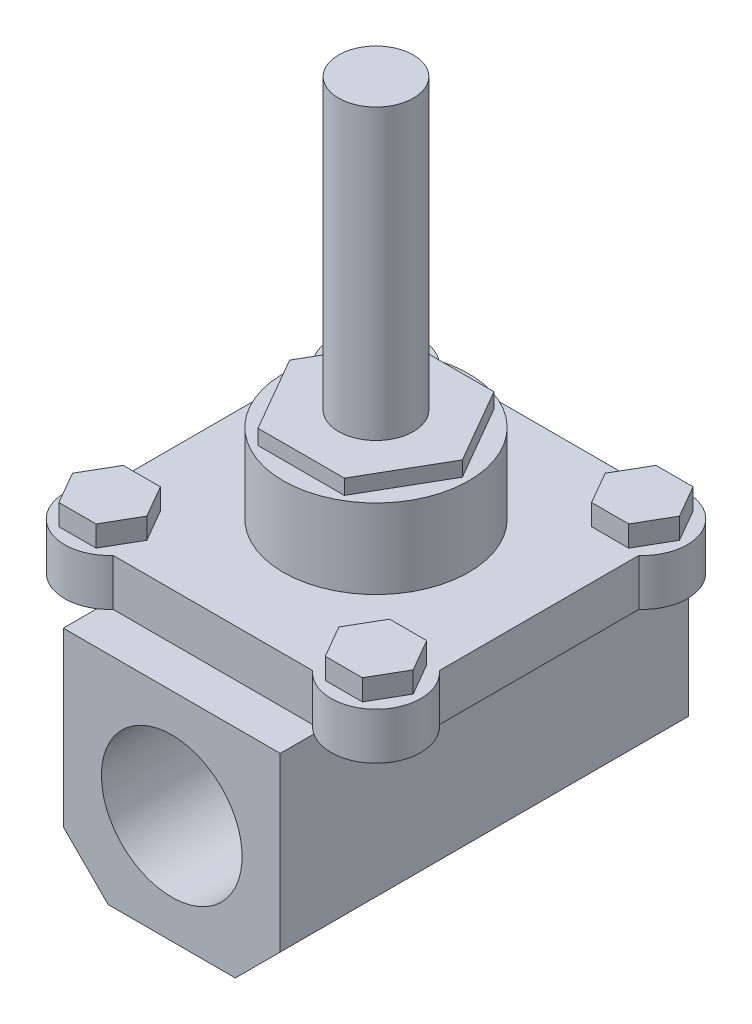
SolidWorks part; units mm, degrees
ref_plane "Front Plane" through (0, 0, 0) normal (0, 0, 1) x (1, 0, 0)
ref_plane "Top Plane" through (0, 0, 0) normal (0, 1, 0) x (1, 0, 0)
ref_plane "Right Plane" through (0, 0, 0) normal (1, 0, 0) x (0, 0, -1)
sketch "Sketch1" plane through (0, 0, 0) normal (0, 1, 0) x (1, 0, 0)
  line L0 (-22.606, 22.606) -> (-27.686, 27.686) construction
  line L1 (16.9264, 27.686) -> (-16.9264, 27.686)
  line L2 (27.686, 16.9264) -> (27.686, -16.9264)
  line L3 (16.9264, -27.686) -> (-16.9264, -27.686)
  line L4 (-27.686, 16.9264) -> (-27.686, -16.9264)
  line L5 (27.686, 27.686) -> (-27.686, -27.686) construction
  line L6 (27.686, -27.686) -> (0, 0) construction
  line L11 (-27.9942, 27.9942) -> (-22.606, 22.606) construction
  line L12 (-30.226, -30.226) -> (30.226, 30.226) construction
  line L13 (22.606, 22.606) -> (-22.606, 22.606) construction
  line L14 (22.606, 22.606) -> (22.606, -22.606) construction
  line L15 (22.606, -22.606) -> (-22.606, -22.606) construction
  line L16 (-22.606, 22.606) -> (-22.606, -22.606) construction
  line L17 (22.606, 22.606) -> (-22.606, -22.606) construction
  line L18 (22.606, -22.606) -> (0, 0) construction
  line L19 (0, 0) -> (30.226, -30.226) construction
  arc A0 (-16.9264, 27.686) -> (-27.686, 16.9264) centre (-22.606, 22.606) ccw
  arc A3 (-27.686, -16.9264) -> (-16.9264, -27.686) centre (-22.606, -22.606) ccw
  arc A4 (27.686, 16.9264) -> (16.9264, 27.686) centre (22.606, 22.606) ccw
  arc A5 (16.9264, -27.686) -> (27.686, -16.9264) centre (22.606, -22.606) ccw
  point P0 (0, 0)
  point P6 (0, 0)
  point P11 (0, 0)
  dimension "D3" = 15.24
  dimension "D1" = 55.372
  dimension "D2" = 60.452
extrude "Boss-Extrude1" add sketch "Sketch1" along normal blind 7.9375
sketch "Sketch2" plane through (0, 0, 27.686) normal (0, 0, 1) x (1, 0, 0)
  line L0 (0, 0) -> (0, -20.5822) construction
  line L1 (-16.9264, 0) -> (16.9264, 0) construction
  line L2 (-18.415, -36.83) -> (18.415, -36.83)
  line L3 (-18.415, -36.83) -> (-18.415, 0)
  line L4 (-18.415, 0) -> (18.415, 0)
  line L5 (18.415, -36.83) -> (18.415, 0)
  line L6 (-18.415, -36.83) -> (18.415, 0) construction
  line L7 (-18.415, 0) -> (18.415, -36.83) construction
  point P2 (0, -18.415)
  dimension "D1" = 36.83
extrude "Boss-Extrude2" add sketch "Sketch2" against normal blind 62.357 and the other way blind 6.985 separate body
sketch "Sketch3" plane through (0, 0, -34.671) normal (0, 0, -1) x (-1, 0, 0)
  line L0 (-18.415, 0) -> (18.415, -36.83) construction
  circle A0 centre (0, -18.415) radius 11.938
  dimension "D1" = 23.876
extrude "Cut-Extrude1" cut sketch "Sketch3" against normal through all
sketch "Sketch6" plane through (0, 7.9375, 0) normal (0, 1, 0) x (1, 0, 0)
  line L1 (22.606, -22.606) -> (-22.606, -22.606) construction
  line L2 (22.606, -22.606) -> (22.606, 22.606) construction
  line L3 (22.606, 22.606) -> (-22.606, 22.606) construction
  line L4 (-22.606, -22.606) -> (-22.606, 22.606) construction
  line L5 (16.3002, -22.606) -> (19.4531, -28.067)
  line L6 (19.4531, -28.067) -> (25.7589, -28.067)
  line L7 (25.7589, -28.067) -> (28.9118, -22.606)
  line L8 (28.9118, -22.606) -> (25.7589, -17.145)
  line L9 (25.7589, -17.145) -> (19.4531, -17.145)
  line L10 (19.4531, -17.145) -> (16.3002, -22.606)
  line L11 (-16.3002, -22.606) -> (-19.4531, -17.145)
  line L12 (-19.4531, -17.145) -> (-25.7589, -17.145)
  line L13 (-25.7589, -17.145) -> (-28.9118, -22.606)
  line L14 (-28.9118, -22.606) -> (-25.7589, -28.067)
  line L15 (-25.7589, -28.067) -> (-19.4531, -28.067)
  line L16 (-19.4531, -28.067) -> (-16.3002, -22.606)
  line L17 (-16.3002, 22.606) -> (-19.4531, 28.067)
  line L18 (-19.4531, 28.067) -> (-25.7589, 28.067)
  line L19 (-25.7589, 28.067) -> (-28.9118, 22.606)
  line L20 (-28.9118, 22.606) -> (-25.7589, 17.145)
  line L21 (-25.7589, 17.145) -> (-19.4531, 17.145)
  line L22 (-19.4531, 17.145) -> (-16.3002, 22.606)
  line L23 (16.3002, 22.606) -> (19.4531, 17.145)
  line L24 (19.4531, 17.145) -> (25.7589, 17.145)
  line L25 (25.7589, 17.145) -> (28.9118, 22.606)
  line L26 (28.9118, 22.606) -> (25.7589, 28.067)
  line L27 (25.7589, 28.067) -> (19.4531, 28.067)
  line L28 (19.4531, 28.067) -> (16.3002, 22.606)
  circle A0 centre (22.606, -22.606) radius 5.461 construction
  circle A1 centre (-22.606, -22.606) radius 5.461 construction
  circle A2 centre (-22.606, 22.606) radius 5.461 construction
  circle A3 centre (22.606, 22.606) radius 5.461 construction
  dimension "D1" = 10.922
extrude "Boss-Extrude3" add sketch "Sketch6" along normal blind 3.556
sketch "Sketch7" plane through (0, 7.9375, 0) normal (0, 1, 0) x (1, 0, 0)
  circle A0 centre (0, 0) radius 15.748
  dimension "D1" = 31.496
extrude "Boss-Extrude4" add sketch "Sketch7" along normal blind 13.462
sketch "Sketch8" plane through (0, 21.3995, 0) normal (0, 1, 0) x (1, 0, 0)
  line L1 (14.6647, 0) -> (7.3323, 12.7)
  line L2 (7.3323, 12.7) -> (-7.3323, 12.7)
  line L3 (-7.3323, 12.7) -> (-14.6647, 0)
  line L4 (-14.6647, 0) -> (-7.3323, -12.7)
  line L5 (-7.3323, -12.7) -> (7.3323, -12.7)
  line L6 (7.3323, -12.7) -> (14.6647, 0)
  circle A0 centre (0, 0) radius 12.7 construction
  dimension "D1" = 25.4
extrude "Boss-Extrude5" add sketch "Sketch8" along normal blind 2.54
sketch "Sketch9" plane through (0, 23.9395, 0) normal (0, 1, 0) x (1, 0, 0)
  circle A0 centre (0, 0) radius 6.35
  dimension "D1" = 12.7
extrude "Boss-Extrude6" add sketch "Sketch9" along normal blind 49.022
chamfer "Chamfer1" distance 7.62 angle 45 2 edges at (18.415, -36.83, 0) (-18.415, -36.83, 0)
